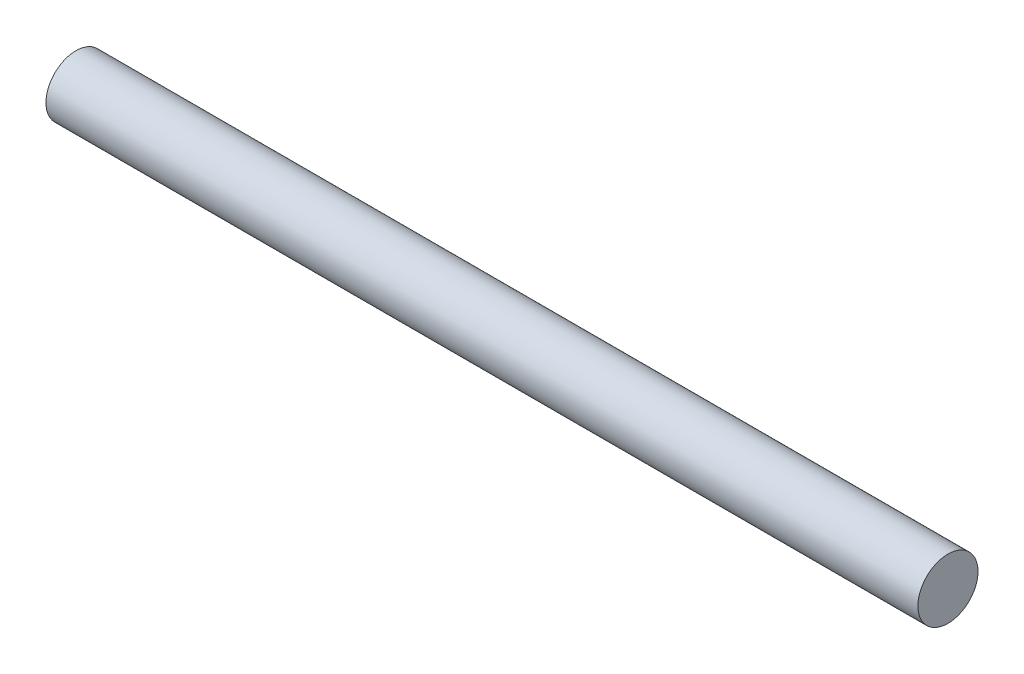
SolidWorks part; units mm, degrees
ref_plane "Front Plane" through (0, 0, 0) normal (0, 0, 1) x (1, 0, 0)
ref_plane "Top Plane" through (0, 0, 0) normal (0, 1, 0) x (1, 0, 0)
ref_plane "Right Plane" through (0, 0, 0) normal (1, 0, 0) x (0, 0, -1)
sketch "Sketch1" plane through (0, 0, 0) normal (1, 0, 0) x (0, 0, -1)
  circle A0 centre (0, 0) radius 1.5875
  dimension "D1" = 3.175
extrude "Boss-Extrude1" add sketch "Sketch1" along normal mid plane 46.0375
